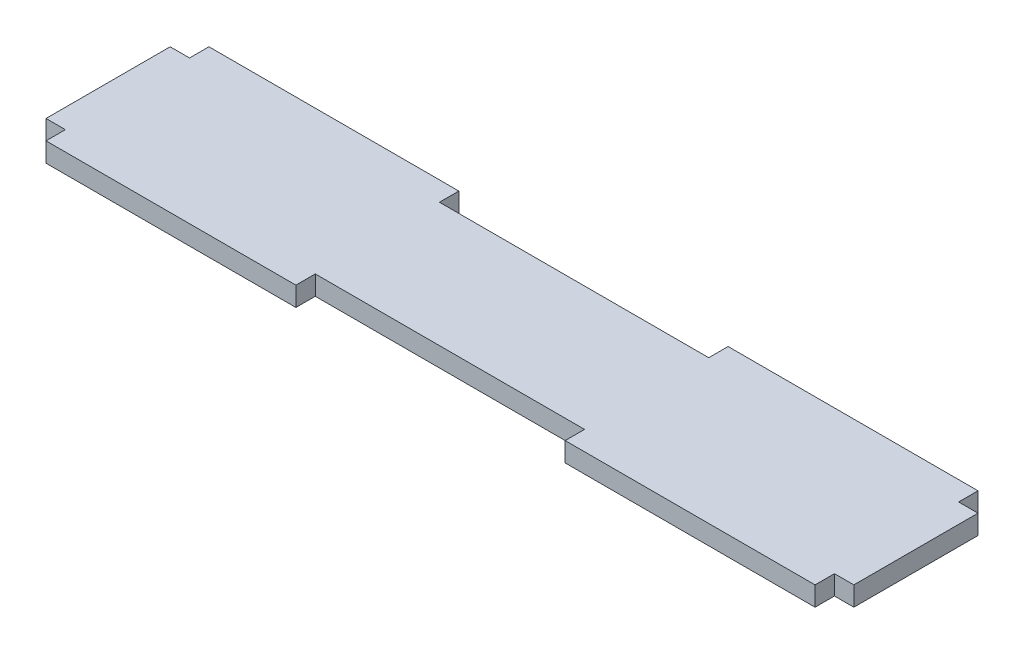
SolidWorks part; units mm, degrees
ref_plane "Front Plane" through (0, 0, 0) normal (0, 0, 1) x (1, 0, 0)
ref_plane "Top Plane" through (0, 0, 0) normal (0, 1, 0) x (1, 0, 0)
ref_plane "Right Plane" through (0, 0, 0) normal (1, 0, 0) x (0, 0, -1)
sketch "Sketch2" plane through (0, 0, 0) normal (0, 1, 0) x (1, 0, 0)
  line L1 (0, 0) -> (500, 0)
  line L2 (0, 0) -> (0, 100.85)
  line L3 (0, 100.85) -> (500, 100.85)
  line L4 (500, 0) -> (500, 100.85)
  dimension "D1" = 100.85
  dimension "D2" = 500
extrude "Boss-Extrude1" add sketch "Sketch2" along normal blind 12
sketch "Sketch4" plane through (0, 12, 0) normal (0, 1, 0) x (1, 0, 0)
  line L1 (500, 0) -> (488, 0)
  line L2 (500, 0) -> (500, 12)
  line L3 (500, 12) -> (488, 12)
  line L4 (488, 0) -> (488, 12)
  line L5 (500, 100.85) -> (488, 100.85)
  line L6 (500, 100.85) -> (500, 88.85)
  line L7 (500, 88.85) -> (488, 88.85)
  line L8 (488, 100.85) -> (488, 88.85)
  line L9 (0, 100.85) -> (12, 100.85)
  line L10 (0, 100.85) -> (0, 88.85)
  line L11 (0, 88.85) -> (12, 88.85)
  line L12 (12, 100.85) -> (12, 88.85)
  line L13 (0, 0) -> (12, 0)
  line L14 (0, 0) -> (0, 12)
  line L15 (0, 12) -> (12, 12)
  line L16 (12, 0) -> (12, 12)
  dimension "D1" = 12
  dimension "D2" = 12
extrude "Cut-Extrude2" cut sketch "Sketch4" against normal through all
sketch "Sketch5" plane through (0, 12, 0) normal (0, 1, 0) x (1, 0, 0)
  line L0 (488, 100.85) -> (12, 100.85) construction
  line L1 (166.6667, 100.85) -> (333.3333, 100.85)
  line L2 (166.6667, 100.85) -> (166.6667, 88.85)
  line L3 (166.6667, 88.85) -> (333.3333, 88.85)
  line L4 (333.3333, 100.85) -> (333.3333, 88.85)
  line L5 (0, 88.85) -> (0, 12) construction
  line L6 (12, 0) -> (488, 0) construction
  line L7 (166.6667, 0) -> (333.3333, 0)
  line L8 (166.6667, 0) -> (166.6667, 12)
  line L9 (166.6667, 12) -> (333.3333, 12)
  line L10 (333.3333, 0) -> (333.3333, 12)
  dimension "D1" = 12
  dimension "D2" = 166.6667
  dimension "D3" = 166.6667
extrude "Cut-Extrude3" cut sketch "Sketch5" against normal through all
scale "Scale1" scale about centroid uniform scaling yes scale factor 0.5
